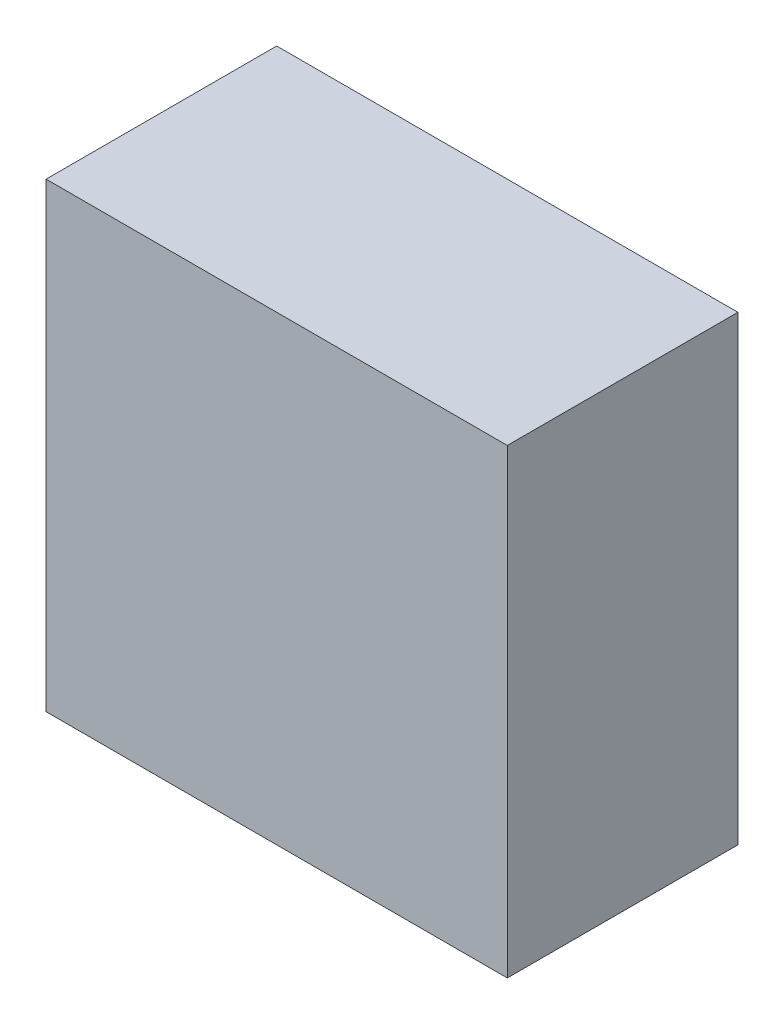
SolidWorks part; units mm, degrees
ref_plane "Front Plane" through (0, 0, 0) normal (0, 0, 1) x (1, 0, 0)
ref_plane "Top Plane" through (0, 0, 0) normal (0, 1, 0) x (1, 0, 0)
ref_plane "Right Plane" through (0, 0, 0) normal (1, 0, 0) x (0, 0, -1)
sketch "Sketch1" plane through (0, 0, 0) normal (0, 0, 1) x (1, 0, 0)
  line L1 (0, 0) -> (300, 0)
  line L2 (0, 0) -> (0, 300)
  line L3 (0, 300) -> (300, 300)
  line L4 (300, 0) -> (300, 300)
  dimension "D1" = 300
  dimension "D2" = 300
extrude "Boss-Extrude1" add sketch "Sketch1" along normal blind 150
